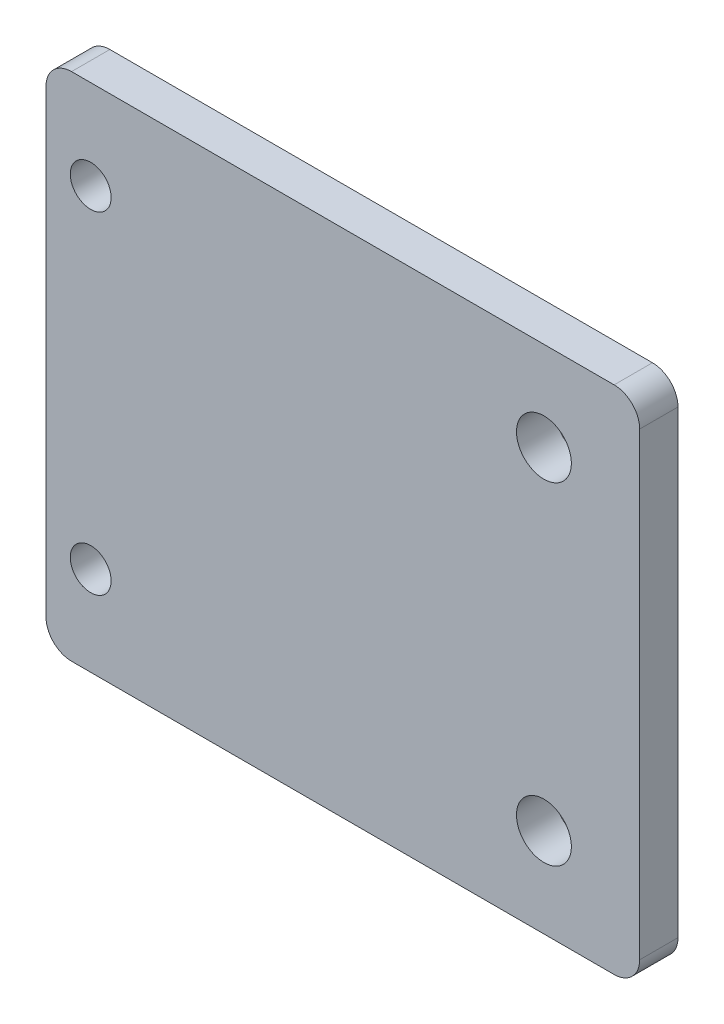
SolidWorks part; units mm, degrees
material "AISI 1045 Steel, cold drawn"
ref_plane "Front Plane" through (0, 0, 0) normal (0, 0, 1) x (1, 0, 0)
ref_plane "Top Plane" through (0, 0, 0) normal (0, 1, 0) x (1, 0, 0)
ref_plane "Right Plane" through (0, 0, 0) normal (1, 0, 0) x (0, 0, -1)
sketch "Sketch1" plane through (0, 0, 0) normal (0, 0, 1) x (1, 0, 0)
  line L1 (23.25, -20) -> (-23.25, -20)
  line L2 (23.25, -20) -> (23.25, 20)
  line L3 (23.25, 20) -> (-23.25, 20)
  line L4 (-23.25, -20) -> (-23.25, 20)
  line L5 (23.25, -20) -> (-23.25, 20) construction
  line L6 (23.25, 20) -> (-23.25, -20) construction
  point P0 (0, 0)
  dimension "D1" = 40
  dimension "D2" = 46.5
extrude "Boss-Extrude1" add sketch "Sketch1" along normal blind 3
sketch "Sketch2" plane through (0, 0, 3) normal (0, 0, 1) x (1, 0, 0)
  line L0 (-23.25, 20) -> (-23.25, -20) construction
  line L1 (15.75, -13) -> (-19.75, -13)
  line L2 (15.75, -13) -> (15.75, 13)
  line L3 (15.75, 13) -> (-19.75, 13)
  line L4 (-19.75, -13) -> (-19.75, 13)
  line L5 (15.75, -13) -> (-19.75, 13) construction
  line L6 (15.75, 13) -> (-19.75, -13) construction
  line L7 (-23.25, 0) -> (-2, 0) construction
  point P0 (-2, 0)
  dimension "D1" = 35.5
  dimension "D2" = 26
  dimension "D3" = 3.5
hole_wizard "M3 Clearance Hole1" positions "Sketch3" profile "Sketch4" hole size "M3" standard "ANSI Metric"
sketch "Sketch3" plane through (0, 0, 3) normal (0, 0, 1) x (1, 0, 0)
  point P0 (-19.75, 13)
  point P3 (-19.75, -13)
sketch "Sketch4" plane through (-19.75, 13, 3) normal (1, 0, 0) x (0, -1, 0)
  line L0 (0, 0) -> (0, 8.9614)
  line L1 (0, 8.9614) -> (1.6, 8)
  line L2 (1.6, 8) -> (1.6, 0)
  line L5 (1.6, 0) -> (0, 0)
  line L10 (0, 8.9614) -> (-1.6, 8) construction
  line L11 (0, -6.35) -> (0, 107.95) construction
  dimension "Hole Dia." = 3.2
  dimension "Hole Depth" = 8
  dimension "Drill Angle" = 118
hole_wizard "M4 Clearance Hole1" positions "Sketch5" profile "Sketch6" hole size "M4" standard "ANSI Metric"
sketch "Sketch5" plane through (0, 0, 3) normal (0, 0, 1) x (1, 0, 0)
  point P0 (15.75, 13)
  point P3 (15.75, -13)
sketch "Sketch6" plane through (15.75, 13, 3) normal (1, 0, 0) x (0, -1, 0)
  line L0 (0, 0) -> (0, 9.2919)
  line L1 (0, 9.2919) -> (2.15, 8)
  line L2 (2.15, 8) -> (2.15, 0)
  line L5 (2.15, 0) -> (0, 0)
  line L10 (0, 9.2919) -> (-2.15, 8) construction
  line L11 (0, -6.35) -> (0, 107.95) construction
  dimension "Hole Dia." = 4.3
  dimension "Hole Depth" = 8
  dimension "Drill Angle" = 118
fillet "Fillet1" radius 2 4 edges at (23.25, 20, 1.5) (23.25, -20, 1.5) (-23.25, -20, 1.5) (-23.25, 20, 1.5)
